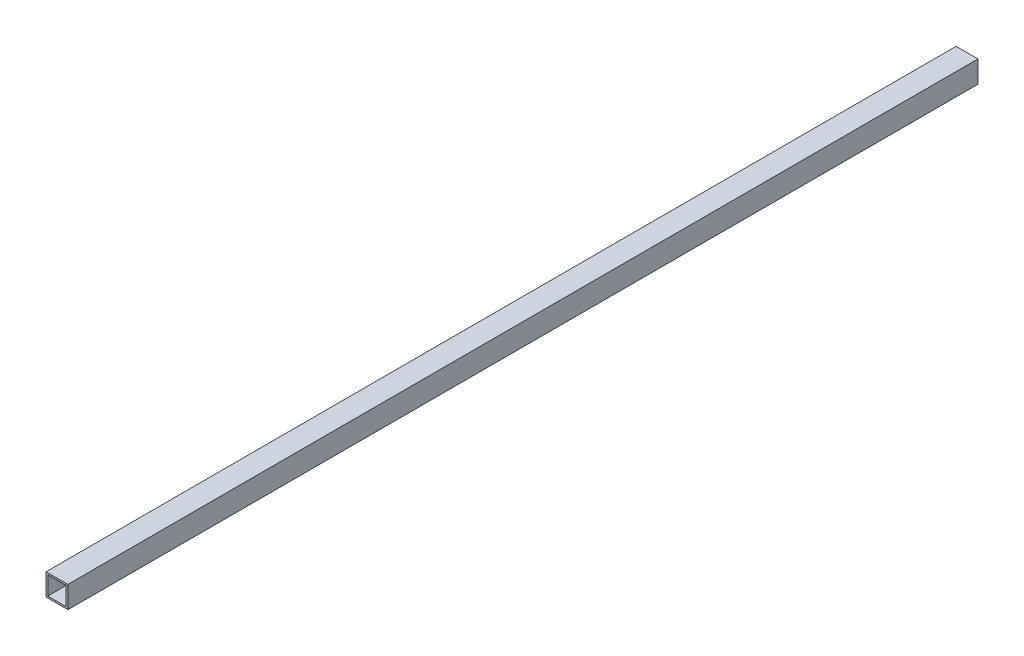
SolidWorks part; units mm, degrees
ref_plane "Front Plane" through (0, 0, 0) normal (0, 0, 1) x (1, 0, 0)
ref_plane "Top Plane" through (0, 0, 0) normal (0, 1, 0) x (1, 0, 0)
ref_plane "Right Plane" through (0, 0, 0) normal (1, 0, 0) x (0, 0, -1)
sketch "Sketch1" plane through (0, 0, 0) normal (0, 0, 1) x (1, 0, 0)
  line L1 (-12.5, -12.5) -> (12.5, -12.5)
  line L2 (-12.5, -12.5) -> (-12.5, 12.5)
  line L3 (-12.5, 12.5) -> (12.5, 12.5)
  line L4 (12.5, -12.5) -> (12.5, 12.5)
  line L5 (-12.5, -12.5) -> (12.5, 12.5) construction
  line L6 (-12.5, 12.5) -> (12.5, -12.5) construction
  line L7 (-10.5, -10.5) -> (10.5, -10.5)
  line L8 (-10.5, -10.5) -> (-10.5, 10.5)
  line L9 (-10.5, 10.5) -> (10.5, 10.5)
  line L10 (10.5, -10.5) -> (10.5, 10.5)
  line L11 (-10.5, -10.5) -> (10.5, 10.5) construction
  line L12 (-10.5, 10.5) -> (10.5, -10.5) construction
  point P0 (0, 0)
  point P6 (0, 0)
  dimension "D1" = 25
  dimension "D2" = 21
extrude "Boss-Extrude1" add sketch "Sketch1" along normal mid plane 1040
sketch "Sketch2" plane through (0, 0, 520) normal (0, 0, 1) x (1, 0, 0)
  line L0 (12.7, -12.7) -> (12.7, 12.7)
  line L1 (12.7, 12.7) -> (-12.7, 12.7)
  line L2 (-12.7, 12.7) -> (-12.7, -12.7)
  line L3 (-12.7, -12.7) -> (12.7, -12.7)
  line L4 (12.5, -12.5) -> (12.5, 12.5)
  line L5 (12.5, 12.5) -> (-12.5, 12.5)
  line L6 (-12.5, 12.5) -> (-12.5, -12.5)
  line L7 (-12.5, -12.5) -> (12.5, -12.5)
  line L8 (12.5, -12.5) -> (12.5, 12.5) construction
  line L9 (12.5, 12.5) -> (-12.5, 12.5) construction
  line L10 (-12.5, 12.5) -> (-12.5, -12.5) construction
  line L11 (-12.5, -12.5) -> (12.5, -12.5) construction
  line L12 (31.7, -31.7) -> (31.7, 31.7)
  line L13 (31.7, 31.7) -> (-31.7, 31.7)
  line L14 (-31.7, 31.7) -> (-31.7, -31.7)
  line L15 (-31.7, -31.7) -> (31.7, -31.7)
  line L16 (31.9, -31.9) -> (31.9, 31.9)
  line L17 (31.9, 31.9) -> (-31.9, 31.9)
  line L18 (-31.9, 31.9) -> (-31.9, -31.9)
  line L19 (-31.9, -31.9) -> (31.9, -31.9)
  line L20 (33.9, -33.9) -> (33.9, 33.9)
  line L21 (33.9, 33.9) -> (-33.9, 33.9)
  line L22 (-33.9, 33.9) -> (-33.9, -33.9)
  line L23 (-33.9, -33.9) -> (33.9, -33.9)
  line L24 (0, -33.9) -> (0, 33.9) construction
  line L25 (-33.9, 0) -> (33.9, 0) construction
  line L26 (3.2, -33.9) -> (3.2, -31.9)
  line L27 (-33.9, -3.2) -> (-31.9, -3.2)
  line L28 (-3.2, -33.9) -> (-3.2, -31.9)
  line L29 (-33.9, 3.2) -> (-31.9, 3.2)
  line L30 (-33.9, 6.2) -> (-31.9, 6.2)
  line L31 (-6.2, -33.9) -> (-6.2, -31.9)
  line L32 (-33.9, -6.2) -> (-31.9, -6.2)
  line L33 (6.2, -33.9) -> (6.2, -31.9)
  line L34 (-6.2, -12.5) -> (-6.2, 12.5)
  line L35 (-6.2, -33.9) -> (-6.2, 33.9) construction
  line L36 (-3.2, -12.5) -> (-3.2, 12.5)
  line L37 (-3.2, -33.9) -> (-3.2, 33.9) construction
  line L38 (3.2, -12.5) -> (3.2, 12.5)
  line L39 (3.2, -33.9) -> (3.2, 33.9) construction
  line L40 (6.2, -12.5) -> (6.2, 12.5)
  line L41 (6.2, -33.9) -> (6.2, 33.9) construction
  line L42 (-6.2, -31.7) -> (-6.2, -12.7)
  line L43 (-3.2, -31.7) -> (-3.2, -12.7)
  line L44 (3.2, -31.7) -> (3.2, -12.7)
  line L45 (6.2, -31.7) -> (6.2, -12.7)
  line L46 (31.9, -6.2) -> (33.9, -6.2)
  line L47 (31.9, -3.2) -> (33.9, -3.2)
  line L48 (-33.9, -6.2) -> (33.9, -6.2) construction
  line L49 (31.9, 6.2) -> (33.9, 6.2)
  line L50 (-33.9, -3.2) -> (33.9, -3.2) construction
  line L51 (31.9, 3.2) -> (33.9, 3.2)
  line L52 (-33.9, 6.2) -> (33.9, 6.2) construction
  line L53 (12.7, -6.2) -> (31.7, -6.2)
  line L54 (-33.9, 3.2) -> (33.9, 3.2) construction
  line L55 (12.7, -3.2) -> (31.7, -3.2)
  line L56 (12.7, 3.2) -> (31.7, 3.2)
  line L57 (12.7, 6.2) -> (31.7, 6.2)
  line L58 (3.2, 12.7) -> (3.2, 31.7)
  line L59 (6.2, 12.7) -> (6.2, 31.7)
  line L60 (-6.2, 12.7) -> (-6.2, 31.7)
  line L61 (-3.2, 12.7) -> (-3.2, 31.7)
  line L62 (6.2, 31.9) -> (6.2, 33.9)
  line L63 (3.2, 31.9) -> (3.2, 33.9)
  line L64 (-3.2, 31.9) -> (-3.2, 33.9)
  line L65 (-6.2, 31.9) -> (-6.2, 33.9)
  line L66 (-31.7, 3.2) -> (-12.7, 3.2)
  line L67 (-31.7, 6.2) -> (-12.7, 6.2)
  line L68 (-31.7, -6.2) -> (-12.7, -6.2)
  line L69 (-31.7, -3.2) -> (-12.7, -3.2)
  line L70 (-12.5, -6.2) -> (12.5, -6.2)
  line L71 (-12.5, -3.2) -> (12.5, -3.2)
  line L72 (-12.5, 3.2) -> (12.5, 3.2)
  line L73 (-12.5, 6.2) -> (12.5, 6.2)
  point P24 (0, 0)
  point P28 (0, 0)
  dimension "D1" = 0
  dimension "D2" = 0.2
  dimension "D3" = 19
  dimension "D4" = 0.2
  dimension "D5" = 2
  dimension "D6" = 3.2
  dimension "D7" = 3.2
  dimension "D8" = 3
  dimension "D9" = 3
sketch "Sketch3" plane through (0, 12.5, 0) normal (0, 1, 0) x (1, 0, 0)
  line L0 (-75, 520) -> (75, 520)
  line L1 (-75, -500) -> (75, -500)
  line L2 (-75, -500) -> (-75, 500)
  line L3 (-75, 500) -> (75, 500)
  line L4 (75, -500) -> (75, 500)
  line L5 (-75, -500) -> (75, 500) construction
  line L6 (-75, 500) -> (75, -500) construction
  line L7 (-75, -520) -> (75, -520)
  point P0 (0, 0)
  dimension "D1" = 150
  dimension "D2" = 1000
  dimension "D3" = 20
  dimension "D4" = 20
